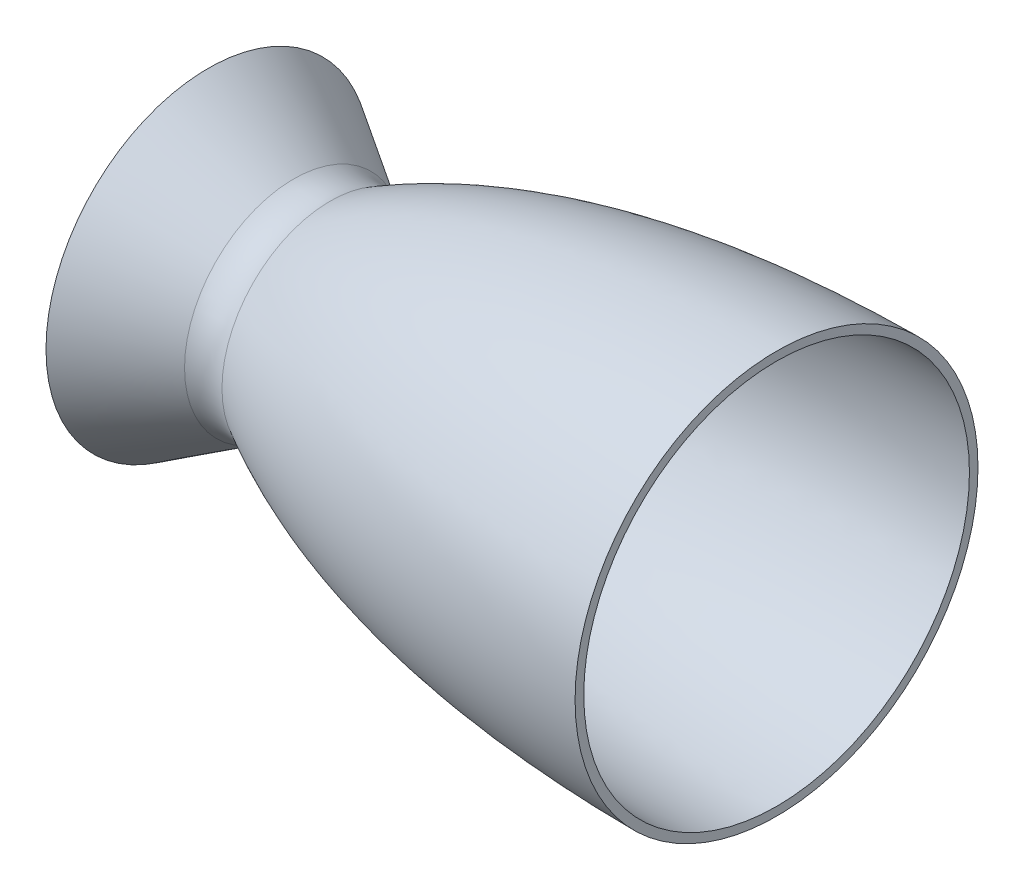
SolidWorks part; units mm, degrees
ref_plane "Front Plane" through (0, 0, 0) normal (0, 0, 1) x (1, 0, 0)
ref_plane "Top Plane" through (0, 0, 0) normal (0, 1, 0) x (1, 0, 0)
ref_plane "Right Plane" through (0, 0, 0) normal (1, 0, 0) x (0, 0, -1)
curve "Curve1"
  spline degree 3 poles (0, 35, 0) (0.5916, 35.3235, 0) (1.6039, 35.8771, 0) (3.0513, 36.6509, 0) (4.3461, 37.3307, 0) (5.6675, 38.0116, 0) (7.0164, 38.6935, 0) (8.3937, 39.3764, 0) (9.8005, 40.0603, 0) (11.2378, 40.7449, 0) (12.7066, 41.4304, 0) (14.2081, 42.1164, 0) (15.7434, 42.803, 0) (17.3137, 43.49, 0) (18.9203, 44.1773, 0) (20.5645, 44.8646, 0) (22.2476, 45.5519, 0) (23.9711, 46.2388, 0) (25.7363, 46.9253, 0) (27.5449, 47.611, 0) (29.3984, 48.2957, 0) (31.2984, 48.9791, 0) (33.2467, 49.661, 0) (35.2451, 50.341, 0) (37.2955, 51.0187, 0) (39.3998, 51.6938, 0) (41.56, 52.3658, 0) (43.7784, 53.0343, 0) (46.0571, 53.6988, 0) (48.3984, 54.3589, 0) (50.8049, 55.0139, 0) (53.279, 55.6633, 0) (55.8236, 56.3064, 0) (58.4413, 56.9426, 0) (61.1351, 57.5711, 0) (63.9081, 58.1911, 0) (66.7636, 58.8017, 0) (69.7051, 59.4021, 0) (72.7359, 59.9914, 0) (75.8601, 60.5683, 0) (79.0815, 61.132, 0) (82.4043, 61.681, 0) (85.833, 62.2142, 0) (89.3722, 62.7302, 0) (93.0268, 63.2275, 0) (96.802, 63.7044, 0) (100.7034, 64.1594, 0) (104.7367, 64.5906, 0) (108.9082, 64.9959, 0) (113.2243, 65.3734, 0) (117.692, 65.7206, 0) (122.3187, 66.0352, 0) (127.1122, 66.3146, 0) (132.0807, 66.5558, 0) (137.2333, 66.7561, 0) (142.5793, 66.9109, 0) (148.1288, 67.0215, 0) (151.8976, 67.0503, 0) (153.8176, 67.0649, 0) knots 0 0 0 0 0.012743 0.021807 0.031019 0.040381 0.049901 0.059584 0.069436 0.079463 0.089672 0.100069 0.110662 0.121457 0.132463 0.143687 0.155137 0.166822 0.178751 0.190933 0.203377 0.216094 0.229095 0.242389 0.255989 0.269907 0.284155 0.298746 0.313694 0.329014 0.344721 0.360829 0.377358 0.394322 0.411742 0.429636 0.448025 0.466929 0.486373 0.506378 0.526972 0.548179 0.570029 0.59255 0.615774 0.639734 0.664466 0.690007 0.716395 0.743675 0.771889 0.801086 0.831317 0.862635 0.895099 0.928769 0.963713 1 1 1 1
sketch "Sketch1" plane through (0, 0, 0) normal (0, 0, 1) x (1, 0, 0)
  line L0 (-14.1132, 37.9758) -> (-43.8668, 56.4075)
  line L1 (-15.6931, 35.4255) -> (-45.4466, 53.8572)
  line L2 (-45.4466, 53.8572) -> (-43.8668, 56.4075)
  line L3 (153.7947, 70.0648) -> (153.8176, 67.0649)
  line L4 (-85.9164, 0) -> (248.6762, 0) construction
  arc A0 (-14.1132, 37.9758) -> (-1.4394, 37.6322) centre (-7.4079, 51.3936) ccw
  arc A1 (-15.6931, 35.4255) -> (0, 35) centre (-7.4079, 51.3936) ccw
  spline S0 degree 3 poles (-1589.6651, 2574.8225) (-94.1586, -53.1352) (-53.7095, 6.3039) (3.0513, 36.6509) (4.3461, 37.3307) (6.5864, 38.485) (8.8832, 39.6233) (11.2378, 40.7449) (13.2145, 41.6674) (15.2393, 42.5825) (17.3137, 43.49) (19.4774, 44.4155) (22.2793, 45.5729) (25.1582, 46.7061) (27.5449, 47.611) (30.0436, 48.5341) (32.6097, 49.4443) (35.2451, 50.341) (37.2955, 51.0187) (40.1349, 51.9296) (43.8298, 53.0605) (47.6352, 54.1512) (50.8049, 55.0139) (53.279, 55.6633) (56.7172, 56.5323) (60.2591, 57.3752) (64.8843, 58.4093) (69.7862, 59.4328) (74.8467, 60.391) (79.0815, 61.132) (82.4043, 61.681) (85.833, 62.2142) (89.3722, 62.7302) (93.0268, 63.2275) (96.802, 63.7044) (100.7034, 64.1594) (104.7367, 64.5906) (108.9082, 64.9959) (113.2243, 65.3734) (117.692, 65.7206) (122.3187, 66.0352) (127.1122, 66.3146) (132.0807, 66.5558) (137.2333, 66.7561) (142.5793, 66.9109) (268.5932, 69.4206) (393.4543, 21.615) (478.1862, 3036.5091) knots -1.185415 -1.185415 -1.185415 -1.185415 0.012743 0.021807 0.031019 0.040381 0.069436 0.079463 0.089672 0.110662 0.121457 0.132463 0.155137 0.178751 0.190933 0.203377 0.229095 0.242389 0.255989 0.269907 0.298746 0.329014 0.344721 0.360829 0.377358 0.411742 0.429636 0.466929 0.506378 0.526972 0.548179 0.570029 0.59255 0.615774 0.639734 0.664466 0.690007 0.716395 0.743675 0.771889 0.801086 0.831317 0.862635 0.895099 0.928769 0.963713 3.277113 3.277113 3.277113 3.277113 only from (0, 35) to (153.8176, 67.0649) construction
  spline S1 degree 3 poles (0, 35) (0.5916, 35.3235) (1.6039, 35.8771) (3.0513, 36.6509) (4.3461, 37.3307) (6.5864, 38.485) (8.8832, 39.6233) (11.2378, 40.7449) (13.2145, 41.6674) (15.2393, 42.5825) (17.3137, 43.49) (19.4774, 44.4155) (22.2793, 45.5729) (25.1582, 46.7061) (27.5449, 47.611) (30.0436, 48.5341) (32.6097, 49.4443) (35.2451, 50.341) (37.2955, 51.0187) (40.1349, 51.9296) (43.8298, 53.0605) (47.6352, 54.1512) (50.8049, 55.0139) (53.279, 55.6633) (56.7172, 56.5323) (60.2591, 57.3752) (64.8843, 58.4093) (69.7862, 59.4328) (74.8467, 60.391) (79.0815, 61.132) (82.4043, 61.681) (85.833, 62.2142) (89.3722, 62.7302) (93.0268, 63.2275) (96.802, 63.7044) (100.7034, 64.1594) (104.7367, 64.5906) (108.9082, 64.9959) (113.2243, 65.3734) (117.692, 65.7206) (122.3187, 66.0352) (127.1122, 66.3146) (132.0807, 66.5558) (137.2333, 66.7561) (142.5793, 66.9109) (148.1288, 67.0215) (151.8976, 67.0503) (153.8176, 67.0649) knots 0 0 0 0 0.012743 0.021807 0.031019 0.040381 0.069436 0.079463 0.089672 0.110662 0.121457 0.132463 0.155137 0.178751 0.190933 0.203377 0.229095 0.242389 0.255989 0.269907 0.298746 0.329014 0.344721 0.360829 0.377358 0.411742 0.429636 0.466929 0.506378 0.526972 0.548179 0.570029 0.59255 0.615774 0.639734 0.664466 0.690007 0.716395 0.743675 0.771889 0.801086 0.831317 0.862635 0.895099 0.928769 0.963713 1 1 1 1
  spline S2 degree 1 poles (-1.4394, 37.6322) (153.7947, 70.0648) knots 0 0 1 1 construction
  spline S3 degree 3 poles (-1.4394, 37.6322) (0.0297, 38.4355) (2.9739, 40.0233) (8.98, 43.0445) (19.6578, 47.9317) (35.3605, 53.821) (54.6635, 59.3412) (80.7989, 64.9122) (107.2855, 68.1875) (130.5363, 69.5516) (143.8334, 69.9662) (150.4733, 70.0395) (153.7947, 70.0648) knots 0 0 0 0 0.03125 0.0625 0.125 0.25 0.375 0.5 0.75 0.875 0.9375 1 1 1 1
  point P13 (-14.8157, 35)
  dimension "D4" = 15
  dimension "D3" = 35
  dimension "D1" = 3
  dimension "D2" = 3
revolve "Revolve1" add sketch "Sketch1" angle 360 about L4
